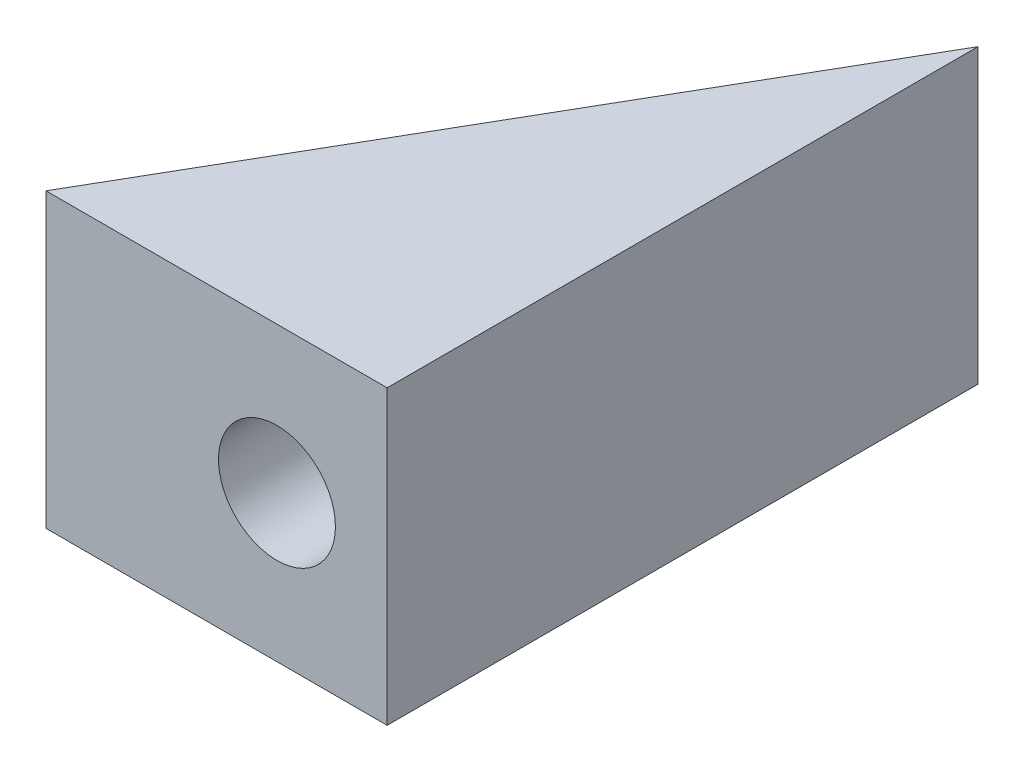
SolidWorks part; units mm, degrees
ref_plane "Front Plane" through (0, 0, 0) normal (0, 0, 1) x (1, 0, 0)
ref_plane "Top Plane" through (0, 0, 0) normal (0, 1, 0) x (1, 0, 0)
ref_plane "Right Plane" through (0, 0, 0) normal (1, 0, 0) x (0, 0, -1)
sketch "Sketch1" plane through (0, 0, 0) normal (0, 1, 0) x (1, 0, 0)
  line L0 (-11.6688, 0) -> (0, 20.211)
  line L1 (0, 20.211) -> (0, 0)
  line L2 (0, 0) -> (-11.6688, 0)
extrude "Boss-Extrude2" add sketch "Sketch1" along normal blind 10 contours L0 L1 L2
sketch "Sketch2" plane through (0, 0, 0) normal (0, 0, 1) x (1, 0, 0)
  line L0 (-11.6688, 5) -> (-3.7688, 5)
  line L1 (-11.6688, 10) -> (-11.6688, 0) construction
  circle A0 centre (-3.7688, 5) radius 2
hole_wizard "Ø4.0mm Dowel Hole1" positions "3DSketch2" profile "Sketch5" hole size "Ø4.0" standard "ANSI Metric"
sketch3d "3DSketch2"
  point P0 (-3.7688, 5, 0)
sketch "Sketch5" plane through (-3.7688, 5, 0) normal (1, 0, 0) x (0, -1, 0)
  line L0 (0, 0) -> (0, 8.2017)
  line L1 (0, 8.2017) -> (2, 7)
  line L2 (2, 7) -> (2, 0)
  line L5 (2, 0) -> (0, 0)
  line L10 (0, 8.2017) -> (-2, 7) construction
  line L11 (0, -6.35) -> (0, 107.95) construction
  dimension "Hole Dia." = 4
  dimension "Hole Depth" = 7
  dimension "Drill Angle" = 118
sketch "Sketch6" plane through (-8.7516, 0, -5.0528) normal (-0.866, 0, -0.5) x (-0.5, 0, 0.866)
  line L0 (-6.6083, 0) -> (-6.6083, 10)
  line L1 (5.8344, 0) -> (-17.5032, 0) construction
  line L2 (5.8344, 10) -> (-17.5032, 10) construction
hole_wizard "Ø4.0mm Dowel Hole2" positions "3DSketch3" profile "Sketch7" hole size "Ø4.0" standard "ANSI Metric"
sketch3d "3DSketch3"
  line L0 (-5.4475, 0, -10.7757) -> (-5.4475, 10, -10.7757) construction
  point P0 (-5.4475, 5, -10.7757)
  point P5 (-5.4475, 5, -10.7757)
  point P7 (-5.4475, 5, -10.7757)
  point P9 (-5.4475, 5, -10.7757)
  point P11 (-5.4475, 5, -10.7757)
  point P13 (-5.4475, 5, -10.7757)
  point P15 (-5.4475, 5, -10.7757)
  point P17 (-5.4475, 5, -10.7757)
  point P19 (-7.5686, 5.2989, -7.1017)
sketch "Sketch7" plane through (-7.5686, 5.2989, -7.1017) normal (0, 1, 0) x (-0.5, 0, 0.866)
  line L0 (0, 0) -> (0, 8.2017)
  line L1 (0, 8.2017) -> (2, 7)
  line L2 (2, 7) -> (2, 0)
  line L5 (2, 0) -> (0, 0)
  line L10 (0, 8.2017) -> (-2, 7) construction
  line L11 (0, -6.35) -> (0, 107.95) construction
  dimension "Hole Dia." = 4
  dimension "Hole Depth" = 7
  dimension "Drill Angle" = 118
sketch "Sketch8" plane through (-8.7516, 0, -5.0528) normal (-0.866, 0, -0.5) x (-0.5, 0, 0.866)
  line L0 (-0.366, 5.2989) -> (5.8344, 5.2989)
  line L1 (5.8344, 10) -> (5.8344, 0) construction
  circle A0 centre (-2.366, 5.2989) radius 2 construction
